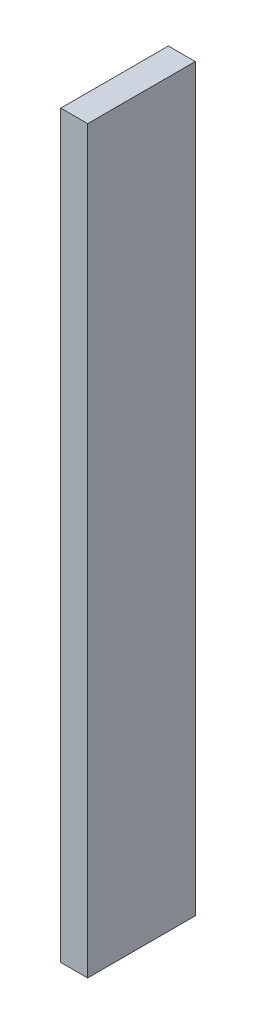
SolidWorks part; units mm, degrees
ref_plane "Front" through (0, 0, 0) normal (0, 0, 1) x (1, 0, 0)
ref_plane "Top" through (0, 0, 0) normal (0, 1, 0) x (1, 0, 0)
ref_plane "Right" through (0, 0, 0) normal (1, 0, 0) x (0, 0, -1)
sketch "草图1" plane through (0, 0, 0) normal (1, 0, 0) x (0, 0, -1)
  line L0 (0, 0) -> (276.8958, 0) construction
  line L1 (-16, 0) -> (16, 0)
  line L2 (-16, 0) -> (-16, 220)
  line L3 (-16, 220) -> (16, 220)
  line L4 (16, 0) -> (16, 220)
  line L5 (0, 0) -> (0, 427.3854) construction
  dimension "D1" = 220
  dimension "D2" = 32
  dimension "D3" = 16
extrude "凸台-拉伸1" add sketch "草图1" along normal blind 8
